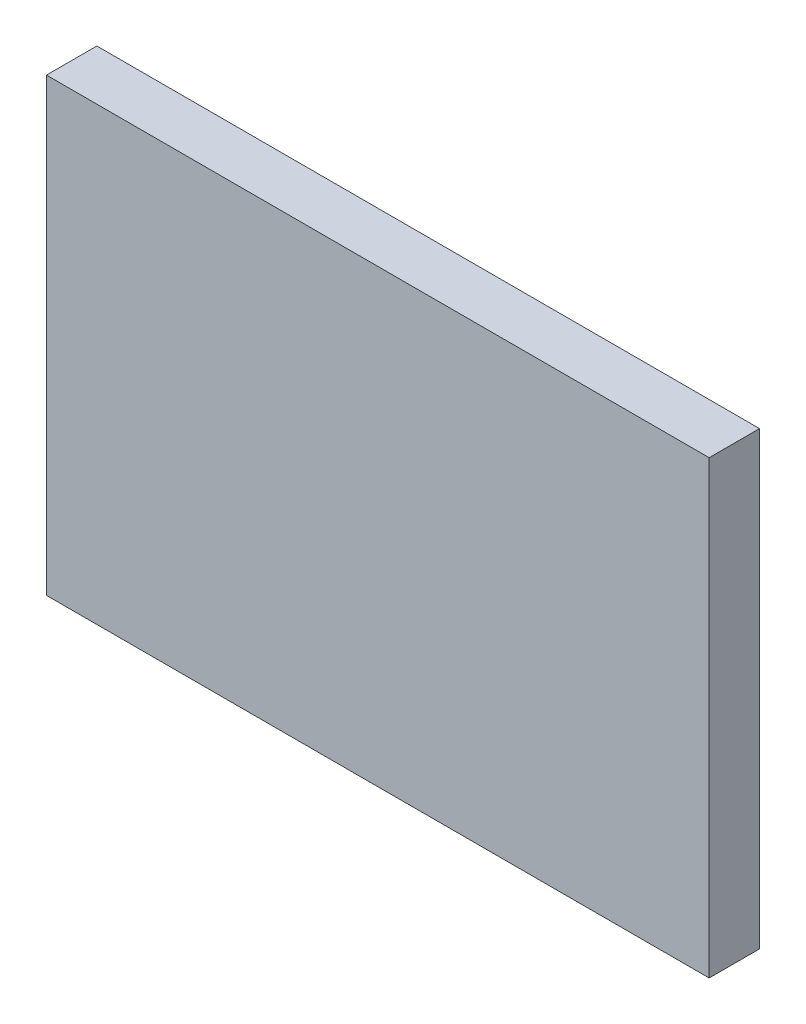
SolidWorks part; units mm, degrees
ref_plane "Спереди" through (0, 0, 0) normal (0, 0, 1) x (1, 0, 0)
ref_plane "Сверху" through (0, 0, 0) normal (0, 1, 0) x (1, 0, 0)
ref_plane "Справа" through (0, 0, 0) normal (1, 0, 0) x (0, 0, -1)
sketch "Эскиз1" plane through (0, 0, 0) normal (0, 0, 1) x (1, 0, 0)
  line L1 (0, 0) -> (45, 0)
  line L2 (0, 0) -> (0, -34)
  line L3 (0, -34) -> (45, -34)
  line L4 (45, 0) -> (45, -34)
  dimension "D1" = 45
  dimension "D2" = 34
extrude "Бобышка-Вытянуть1" add sketch "Эскиз1" along normal blind 3.8
sketch "Эскиз3" plane through (0, 0, 0) normal (0, 0, 1) x (1, 0, 0)
  line L1 (45, -34) -> (50, -34)
  line L2 (45, -34) -> (45, 0)
  line L3 (45, 0) -> (50, 0)
  line L4 (50, -34) -> (50, 0)
  dimension "D1" = 5
  dimension "D2" = 34
extrude "Бобышка-Вытянуть5" add sketch "Эскиз3" along normal blind 3.8
